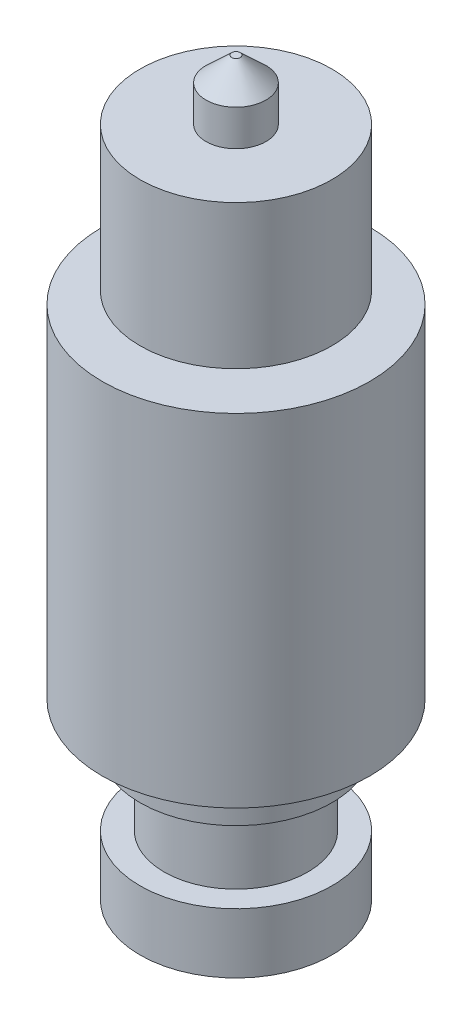
SolidWorks part; units mm, degrees
material "AISI 1035 Steel (SS)"
ref_plane "Front Plane" through (0, 0, 0) normal (0, 0, 1) x (1, 0, 0)
ref_plane "Top Plane" through (0, 0, 0) normal (0, 1, 0) x (1, 0, 0)
ref_plane "Right Plane" through (0, 0, 0) normal (1, 0, 0) x (0, 0, -1)
sketch "Sketch1" plane through (0, 0, 0) normal (0, 1, 0) x (1, 0, 0)
  circle A0 centre (0, 0) radius 8
  dimension "D1" = 16
extrude "Boss-Extrude1" add sketch "Sketch1" along normal blind 5
sketch "Sketch2" plane through (0, 5, 0) normal (0, 1, 0) x (1, 0, 0)
  circle A0 centre (0, 0) radius 6
  dimension "D1" = 12
extrude "Boss-Extrude2" add sketch "Sketch2" along normal blind 6
sketch "Sketch3" plane through (0, 11, 0) normal (0, 1, 0) x (1, 0, 0)
  circle A0 centre (0, 0) radius 8
  dimension "D1" = 16
extrude "Boss-Extrude3" add sketch "Sketch3" along normal blind 1.5
sketch "Sketch4" plane through (0, 12.5, 0) normal (0, 1, 0) x (1, 0, 0)
  circle A0 centre (0, 0) radius 5
  dimension "D1" = 10
extrude "Boss-Extrude4" add sketch "Sketch4" along normal blind 2
sketch "Sketch5" plane through (0, 14.5, 0) normal (0, 1, 0) x (1, 0, 0)
  circle A0 centre (0, 0) radius 11.15
  dimension "D1" = 22.3
extrude "Boss-Extrude5" add sketch "Sketch5" along normal blind 28.5
sketch "Sketch6" plane through (0, 43, 0) normal (0, 1, 0) x (1, 0, 0)
  circle A0 centre (0, 0) radius 2
  dimension "D1" = 4
extrude "Boss-Extrude6" add sketch "Sketch6" along normal blind 1
sketch "Sketch7" plane through (0, 44, 0) normal (0, 1, 0) x (1, 0, 0)
  circle A0 centre (0, 0) radius 8
  dimension "D1" = 16
extrude "Boss-Extrude7" add sketch "Sketch7" along normal blind 12
sketch "Sketch8" plane through (0, 56, 0) normal (0, 1, 0) x (1, 0, 0)
  circle A0 centre (0, 0) radius 2.5
  dimension "D1" = 5
extrude "Boss-Extrude8" add sketch "Sketch8" along normal blind 3
sketch "Sketch9" plane through (0, 59, 0) normal (0, 1, 0) x (1, 0, 0)
  circle A0 centre (0, 0) radius 2.5
extrude "Boss-Extrude9" add sketch "Sketch9" along normal blind 2 draft 47
ref_plane "Plane1" through (0, 0, 0) normal (0, 0, 1) x (1, 0, 0)
equation "\"D1@Boss-Extrude5\"=43-12.5-2"
